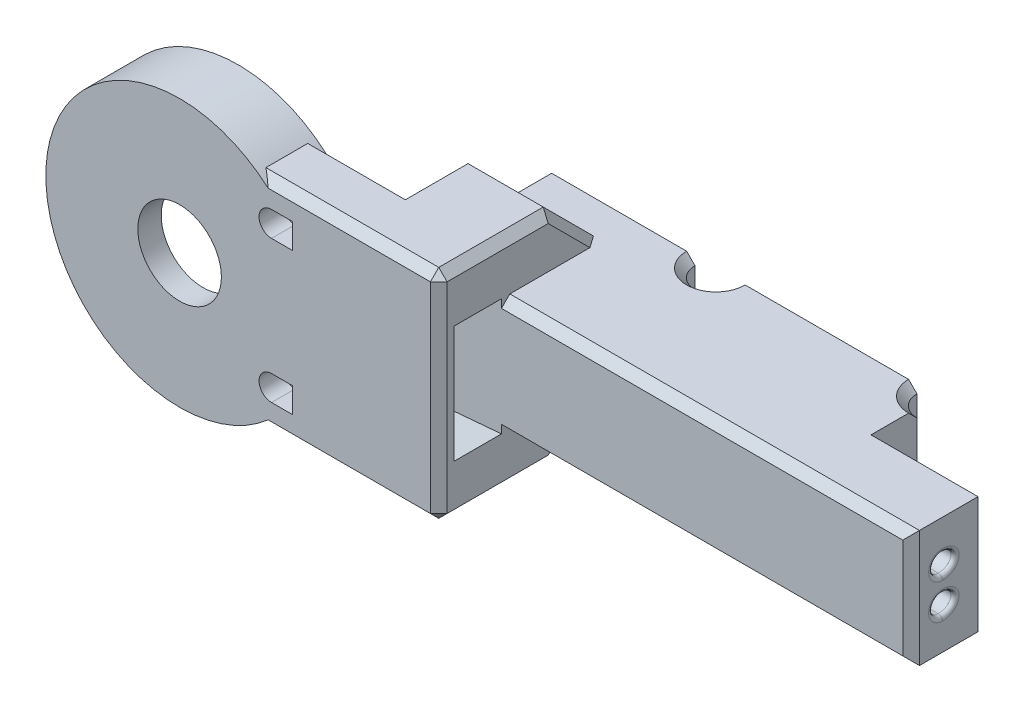
SolidWorks part; units mm, degrees
other "Markup1"
sketch "Sketch31" plane through (-8, 8, 5.05) normal (-0.0551, 0.3318, 0.9417) x (-0.9887, 0.1134, -0.0978)
ref_plane "Front Plane" through (0, 0, 0) normal (0, 0, 1) x (1, 0, 0)
ref_plane "Top Plane" through (0, 0, 0) normal (0, 1, 0) x (1, 0, 0)
ref_plane "Right Plane" through (0, 0, 0) normal (1, 0, 0) x (0, 0, -1)
sketch "Sketch1" plane through (0, 0, 0) normal (0, 0, 1) x (1, 0, 0)
  line L0 (0, 0) -> (15, 0) construction
  line L1 (4.6637, 6.5) -> (15, 6.5)
  line L2 (15, 6.5) -> (15, -6.5)
  line L3 (15, -6.5) -> (4.6637, -6.5)
  line L4 (6.75, 6.5) -> (6.75, -6.5) construction
  line L5 (5.5, 5) -> (6.75, 5)
  line L6 (6.75, 5) -> (6.75, 3.5)
  line L7 (6.75, 3.5) -> (5.5, 3.5)
  line L8 (5.5, -3.5) -> (6.75, -3.5)
  line L9 (6.75, -3.5) -> (6.75, -5)
  line L10 (6.75, -5) -> (5.5, -5)
  circle A0 centre (0, 0) radius 8
  circle A1 centre (0, 0) radius 2.5
  arc A2 (5.5, 5) -> (5.5, 3.5) centre (5.5, 4.25) ccw
  arc A3 (5.5, -3.5) -> (5.5, -5) centre (5.5, -4.25) ccw
  arc A4 (5.5, 3.5) -> (5.5, 5) centre (5.5, 4.25) ccw construction
  arc A5 (5.5, -5) -> (5.5, -3.5) centre (5.5, -4.25) ccw construction
  point P7 (15, 0)
  dimension "D1" = 16
  dimension "D4" = 5
  dimension "D6" = 1.5
  dimension "D7" = 4.25
  dimension "D2" = 15
  dimension "D3" = 13
  dimension "D5" = 6.75
  dimension "D8" = 4.25
  dimension "D9" = 1.25
extrude "Boss-Extrude1" add sketch "Sketch1" along normal blind 3.5 contours A0 L5 L6 L9 L10 L3 L2 L1 | A3 L8 L9 A0 L6 L7 A2 L5 L10 A1
ref_plane "Plane1" through (0, 0, 3.5) normal (0, 0, 1) x (1, 0, 0)
sketch "Sketch39" plane through (0, 0, 0) normal (0, 0, -1) x (-1, 0, 0)
  line L0 (-0.0752, 0) -> (-0.1714, 0) construction
  line L1 (5.75, 0.75) -> (5.75, 2.5)
  line L2 (5.75, 2.5) -> (2.5, 5.75)
  line L3 (2.5, 5.75) -> (-6.75, 5.75)
  line L4 (-6.75, 5.75) -> (-6.75, -5.75)
  line L5 (2.5, -5.75) -> (-6.75, -5.75)
  line L6 (5.75, -2.5) -> (2.5, -5.75)
  line L7 (5.75, 0.75) -> (8.3767, 0.75)
  line L8 (8.3767, 0.75) -> (8.3767, -0.75)
  line L9 (5.75, -0.75) -> (5.75, -2.5)
  line L10 (5.75, -0.75) -> (8.3767, -0.75)
  point P6 (5.75, 0)
  point P15 (-6.75, 0)
  point P19 (8.3767, 0)
  dimension "D1" = 5.75
  dimension "D2" = 5.75
  dimension "D3" = 2.5
  dimension "D4" = 45
  dimension "D5" = 6.75
  dimension "D6" = 0.75
extrude "Cut-Extrude17" cut sketch "Sketch39" against normal blind 2.1
sketch "Sketch38" plane through (15, 0, 0) normal (1, 0, 0) x (0, 0, -1)
  line L0 (-3.5, 6.5) -> (3.25, 6.5)
  line L1 (3.25, 6.5) -> (6.25, 3.5)
  line L2 (6.25, 3.5) -> (8.25, 3.5)
  line L3 (8.25, 3.5) -> (8.25, -3.5)
  line L4 (8.25, -3.5) -> (6.25, -3.5)
  line L5 (6.25, -3.5) -> (3.25, -6.5)
  line L6 (3.25, -6.5) -> (-3.5, -6.5)
  line L7 (0, 6.5) -> (0, -6.5) construction
  line L12 (0, -6.5) -> (0, 6.5)
  line L13 (0, 6.5) -> (-3.5, 6.5)
  line L14 (-3.5, 6.5) -> (-3.5, -6.5)
  line L15 (-3.5, -6.5) -> (0, -6.5)
  line L18 (-3.5, 6.5) -> (-3.5, -6.5)
  point P10 (8.25, 0)
  dimension "D1" = 3.25
  dimension "D2" = 3
  dimension "D3" = 3
  dimension "D4" = 2
  dimension "D5" = 0
extrude "Boss-Extrude11" add sketch "Sketch38" against normal blind 5
sketch "Sketch37" plane through (0, 0, 0) normal (0, 1, 0) x (1, 0, 0)
  line L0 (0, -9.2084) -> (0, 9.2084) construction
  line L3 (-1000, 0) -> (49000, 0) construction
  line L5 (40, 0) -> (40, 50000) construction
  point P4 (0, 0)
ref_plane "Plane2" through (40, 0, 0) normal (1, 0, 0) x (0, 0, -1)
sketch "Sketch6" plane through (15, 0, 0) normal (1, 0, 0) x (0, 0, -1)
  line L1 (3.25, 6.5) -> (-3.5, 6.5)
  line L3 (3.25, -6.5) -> (-3.5, -6.5)
  line L4 (-3.5, 6.5) -> (-3.5, -6.5)
  line L8 (3.25, 6.5) -> (6.25, 3.5)
  line L9 (6.25, 3.5) -> (8.25, 3.5)
  line L10 (0, 8) -> (0, -8) construction
  line L11 (0, 0) -> (8.25, 0) construction
  line L12 (3.25, -6.5) -> (6.25, -3.5)
  line L13 (6.25, -3.5) -> (8.25, -3.5)
  line L14 (8.25, -3.5) -> (8.25, 3.5) construction
  line L15 (3.25, -6.5) -> (6.25, -3.5) construction
  line L16 (8.25, 3.5) -> (6.25, 3.5) construction
  dimension "D1" = 3.25
  dimension "D2" = 3
  dimension "D3" = 3
extrude "Boss-Extrude4" add sketch "Sketch6" along normal up to surface (25 mm away) up to plane "Plane2"
sketch "Sketch7" plane through (0, 0, -8.25) normal (0, 0, -1) x (-1, 0, 0)
  line L1 (-40, -6.5) -> (-31.1, -6.5)
  line L2 (-40, -6.5) -> (-40, 6.5)
  line L3 (-40, 6.5) -> (-31.1, 6.5)
  line L4 (-31.1, -6.5) -> (-31.1, 6.5)
  line L5 (-10, 6.5) -> (-40, 6.5) construction
  dimension "D1" = 8.9
extrude "Cut-Extrude2" cut sketch "Sketch7" against normal blind 4
sketch "Sketch22" plane through (0, 0, 3.5) normal (0, 0, 1) x (1, 0, 0)
  line L1 (15.5, 6.5) -> (40, 6.5)
  line L2 (15.5, 6.5) -> (15.5, -6.5)
  line L3 (15.5, -6.5) -> (40, -6.5)
  line L4 (40, 6.5) -> (40, -6.5)
  line L6 (4.6637, 6.5) -> (40, 6.5) construction
  line L8 (40, -6.5) -> (4.6637, -6.5) construction
  line L9 (10, -3.5) -> (10, 3.5) construction
  dimension "D1" = 5.5
extrude "Cut-Extrude13" cut sketch "Sketch22" against normal blind 3.75 contours L2 L1 L4 L3
sketch "Sketch23" plane through (0, 6.5, 0) normal (0, 1, 0) x (1, 0, 0)
  line L1 (10, 8.25) -> (40, 8.25)
  line L2 (10, 8.25) -> (10, 0.25)
  line L3 (10, 0.25) -> (40, 0.25)
  line L4 (40, 8.25) -> (40, 0.25)
  line L5 (10, 0.25) -> (15.5, 0.25)
  line L6 (10, 0.25) -> (10, 8.25)
  line L7 (10, 8.25) -> (15.5, 8.25)
  line L8 (15.5, 0.25) -> (15.5, 8.25)
  dimension "D2" = 5.5
extrude "Cut-Extrude14" cut sketch "Sketch23" against normal blind 3
mirror "Mirror1" about plane through (0, 0, 0) normal (0, 1, 0) of "Cut-Extrude14"
sketch "Sketch19" plane through (40, 0, 0) normal (1, 0, 0) x (0, 0, -1)
  line L0 (2.125, -3.5) -> (2.125, 3.5) construction
  line L1 (0.25, -3.5) -> (4.25, -3.5) construction
  line L3 (4.25, 3.5) -> (4.25, -3.5) construction
  line L5 (0.25, 3.5) -> (4.25, 3.5) construction
  arc A0 (2.125, -0.475) -> (2.125, -1.625) centre (2.125, -1.05) ccw
  arc A1 (2.125, 1.625) -> (2.125, 0.475) centre (2.125, 1.05) ccw
  arc A2 (2.125, 0.475) -> (2.125, 1.625) centre (2.125, 1.05) ccw construction
  arc A3 (2.125, -1.625) -> (2.125, -0.475) centre (2.125, -1.05) ccw construction
  ellipse E0 centre (2.125, 1.05) end of major axis (2.875, 1.05) minor radius 0.575 (2.125, 0.475) -> (2.125, 1.625) ccw
  ellipse E1 centre (2.125, -1.05) end of major axis (2.875, -1.05) minor radius 0.575 (2.125, -1.625) -> (2.125, -0.475) ccw
  ellipse E2 centre (2.125, 1.05) end of major axis (2.875, 1.05) minor radius 0.575 (2.125, 1.625) -> (2.125, 0.475) ccw construction
  ellipse E3 centre (2.125, -1.05) end of major axis (2.875, -1.05) minor radius 0.575 (2.125, -0.475) -> (2.125, -1.625) ccw construction
  point P11 (2.125, 0)
  dimension "D2" = 1.15
  dimension "D3" = 1.15
  dimension "D1" = 1.05
  dimension "D4" = 2.125
  dimension "D5" = 2.1
  dimension "D6" = 0.75
  dimension "D7" = 0.75
extrude "Cut-Extrude11" cut sketch "Sketch19" against normal through all
sketch "Sketch25" plane through (0, 3.5, 0) normal (0, 1, 0) x (1, 0, 0)
  line L0 (33.6, 7) -> (33.6, 8.25) construction
  line L1 (31.1, 4.25) -> (33.6, 4.25)
  line L2 (31.1, 4.25) -> (31.1, 8.25)
  line L3 (31.1, 8.25) -> (32.35, 8.25)
  line L4 (33.6, 4.25) -> (33.6, 7)
  line L5 (32.35, 8.25) -> (33.6, 8.25) construction
  line L7 (40, 0.25) -> (40, 4.25) construction
  line L8 (10, 8.25) -> (31.1, 8.25) construction
  arc A0 (32.35, 8.25) -> (33.6, 7) centre (33.6, 8.25) ccw
  arc A1 (33.6, 7) -> (32.35, 8.25) centre (33.6, 8.25) ccw construction
  dimension "D1" = 2.5
  dimension "D2" = 6.4
extrude "Boss-Extrude12" add sketch "Sketch25" against normal up to surface (7 mm away) up to face at (24.15, -3.5, -4.75)
sketch "Sketch24" plane through (0, 3.5, 0) normal (0, 1, 0) x (1, 0, 0)
  line L1 (10, 8.25) -> (32.35, 8.25) construction
  line L2 (40, 0.25) -> (40, 4.25) construction
  circle A0 centre (20.325, 8.25) radius 1.25
  dimension "D1" = 2.5
extrude "Cut-Extrude15" cut sketch "Sketch24" against normal through all
sketch "Sketch26" plane through (0, -3.5, 0) normal (0, 1, 0) x (1, 0, 0)
  line L0 (26.75, 8.25) -> (26.75, 3.5) construction
  line L2 (40, 0.25) -> (40, 4.25) construction
  line L3 (28.9, 3.5) -> (24.6, 3.5)
  line L4 (28.9, 3.5) -> (28.9, 8.25)
  line L5 (28.9, 8.25) -> (24.6, 8.25)
  line L6 (24.6, 8.25) -> (24.6, 3.5)
  line L8 (21.575, 8.25) -> (32.35, 8.25) construction
  point P9 (26.75, 3.5)
  dimension "D2" = 4.3
  dimension "D3" = 4.75
extrude "Cut-Extrude16" cut sketch "Sketch26" along normal blind 1.65
ref_plane "Plane6" through (16.75, 0, 0) normal (1, 0, 0) x (0, 0, -1)
fillet "Fillet8" radius 0.25 8 edges at (10, -1.05, -1.55) (10, 1.05, -1.55) (40, -1.05, -1.55) (40, 1.05, -1.55) (10, -1.05, -2.875) (10, 1.05, -2.875) (40, -1.05, -2.875) (40, 1.05, -2.875)
sketch "Sketch40" plane through (15.5, 0, 0) normal (1, 0, 0) x (0, 0, -1)
  line L0 (-3.5, 6.5) -> (-3.5, -6.5) construction
  line L1 (-2.1, 3.5) -> (0.25, 3.5)
  line L2 (-2.1, 3.5) -> (-2.1, -3.5)
  line L3 (-2.1, -3.5) -> (0.25, -3.5)
  line L4 (0.25, 3.5) -> (0.25, -3.5)
  line L5 (0.25, 3.5) -> (0.25, -3.5) construction
  point P4 (0.25, 0)
  dimension "D1" = 7
  dimension "D2" = 1.4
sketch "Sketch41" plane through (6.75, 0, 0) normal (-1, 0, 0) x (0, 0, 1)
  line L0 (3.5, 4.25) -> (2.1, 4.25) construction
  line L1 (2.1, -4.25) -> (-0.25, -4.25)
  line L2 (2.1, -4.25) -> (2.1, 4.25)
  line L3 (2.1, 4.25) -> (-0.25, 4.25)
  line L4 (-0.25, -4.25) -> (-0.25, 4.25)
  line L6 (2.1, 3.5) -> (2.1, -3.5) construction
  line L7 (3.5, -4.25) -> (2.1, -4.25) construction
  dimension "D1" = 2.35
loft "Cut-Loft1" cut profiles "Sketch41", "Sketch40"
chamfer "Chamfer1" distance 0.5 angle 45 27 edges at (10, 6.5, -1.625) (10, 5, -4.75) (10, 3.5, -7.25) (10, 0, -8.25) (10, -3.5, -7.25) (10, -5, -4.75) (10, -6.5, -1.625) (15.5, -5, -4.75) (15.5, 5, -4.75) (15.5, 6.5, 0.125) (15.5, 0, 3.5) (15.5, -6.5, 0.125) (40, 0, -0.25) (24.6, -3.5, -5.875) (26.75, -3.5, -3.5) (28.9, -3.5, -5.875) (32.7161, -3.5, -7.3661) (32.7161, 3.5, -7.3661) (20.325, 3.5, -7) (20.325, -3.5, -7) (7.3318, -6.5, 0) (7.3318, 6.5, 0) (10.0818, -6.5, 3.5) (10.0818, 6.5, 3.5)
equation "\"d\" = 51mm"
equation "\"D1@Sketch37\"=\"d\"-11"
equation "\"phx\"= \"d\" - 11 - 15.5"
equation "\"middle\"= \"phx\" / 2"
equation "\"D1@Sketch26\"=\"middle\" + 1"
equation "\"D2@Sketch24\"=\"middle\" + \"middle\"/2 + 1.3"
